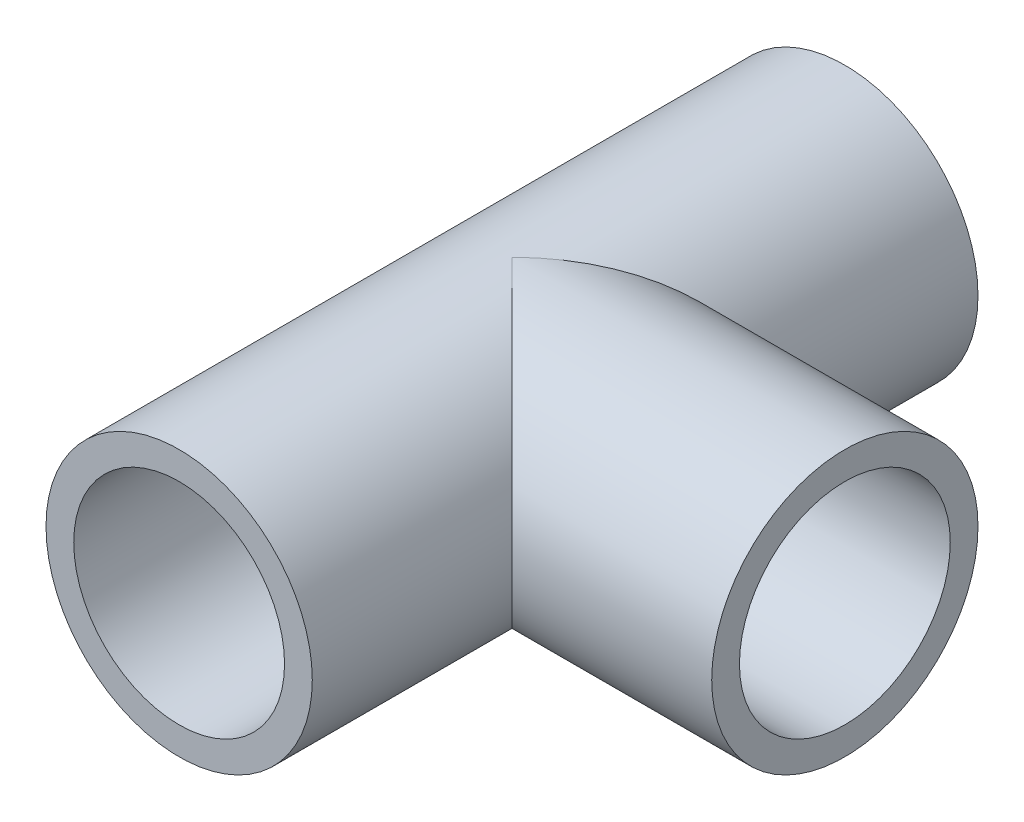
SolidWorks part; units mm, degrees
material "PVC Rigid"
ref_plane "Front Plane" through (0, 0, 0) normal (0, 0, 1) x (1, 0, 0)
ref_plane "Top Plane" through (0, 0, 0) normal (0, 1, 0) x (1, 0, 0)
ref_plane "Right Plane" through (0, 0, 0) normal (1, 0, 0) x (0, 0, -1)
sketch "Sketch1" plane through (0, 0, 0) normal (0, 0, 1) x (1, 0, 0)
  circle A0 centre (0, 0) radius 24.13
  circle A1 centre (0, 0) radius 30.48
  dimension "D1" = 48.26
  dimension "D2" = 6.35
extrude "Boss-Extrude1" add sketch "Sketch1" along normal blind 152.4
ref_plane "Plane1" through (76.2, 0, 0) normal (1, 0, 0) x (0, 0, -1)
sketch "Sketch2" plane through (76.2, 0, 0) normal (1, 0, 0) x (0, 0, -1)
  line L0 (0, -30.48) -> (0, 30.48) construction
  circle A0 centre (-76.2, 0) radius 24.13
  circle A1 centre (-76.2, 0) radius 30.48
  dimension "D1" = 48.26
  dimension "D2" = 6.35
  dimension "D3" = 76.2
extrude "Boss-Extrude2" add sketch "Sketch2" against normal up to next
